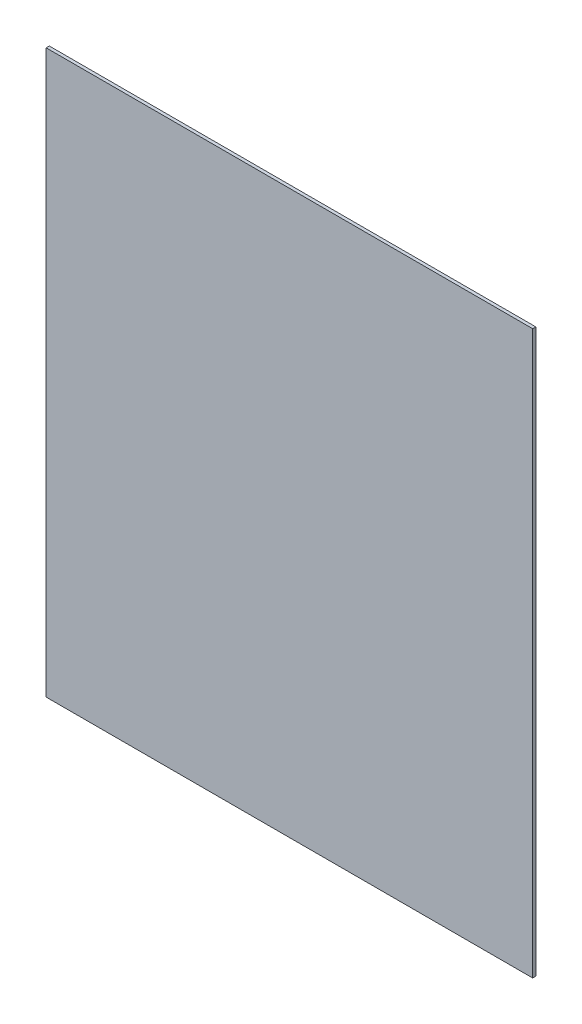
SolidWorks part; units mm, degrees
material "ABS PC"
ref_plane "Front Plane" through (0, 0, 0) normal (0, 0, 1) x (1, 0, 0)
ref_plane "Top Plane" through (0, 0, 0) normal (0, 1, 0) x (1, 0, 0)
ref_plane "Right Plane" through (0, 0, 0) normal (1, 0, 0) x (0, 0, -1)
sketch "Sketch1" plane through (0, 0, 0) normal (0, 0, 1) x (1, 0, 0)
  line L1 (-385, -445) -> (385, -445)
  line L2 (-385, -445) -> (-385, 445)
  line L3 (-385, 445) -> (385, 445)
  line L4 (385, -445) -> (385, 445)
  line L5 (-385, -445) -> (385, 445) construction
  line L6 (-385, 445) -> (385, -445) construction
  point P0 (0, 0)
  dimension "D1" = 770
  dimension "D2" = 890
extrude "Boss-Extrude1" add sketch "Sketch1" along normal blind 5
